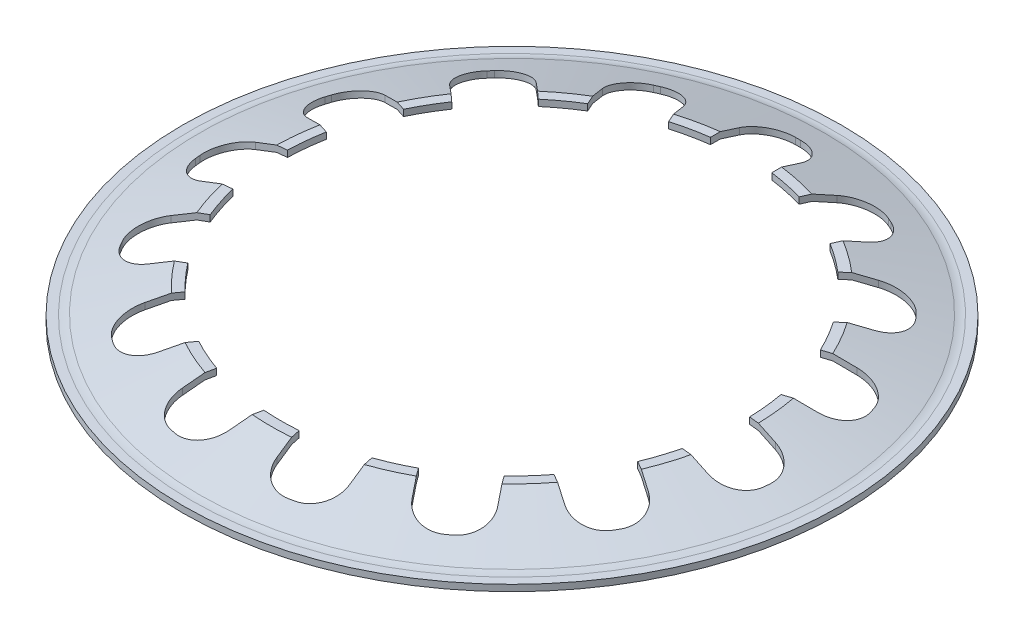
SolidWorks part; units mm, degrees
ref_plane "Plano frontal" through (0, 0, 0) normal (0, 0, 1) x (1, 0, 0)
ref_plane "Plano superior" through (0, 0, 0) normal (0, 1, 0) x (1, 0, 0)
ref_plane "Plano direito" through (0, 0, 0) normal (1, 0, 0) x (0, 0, -1)
sketch "Esboço1" plane through (0, 0, 0) normal (0, 0, 1) x (1, 0, 0)
  line L0 (0, -50.3288) -> (0, 62.2834) construction
  line L1 (47.1561, 13.2438) -> (62, 8.4938)
  line L2 (64.5, 8.4938) -> (64.5, 9.7438)
  line L3 (64.5, 9.7438) -> (62, 9.7438)
  line L4 (62, 9.7438) -> (47.1561, 14.4938)
  line L5 (47.1561, 14.4938) -> (45.25, 14.4938)
  line L6 (45.25, 14.4938) -> (45.25, 13.2438)
  line L7 (45.25, 13.2438) -> (47.1561, 13.2438)
  line L8 (62, 8.4938) -> (64.5, 8.4938)
  dimension "D1" = 1.25
  dimension "D2" = 1.25
  dimension "D3" = 64.5
  dimension "D4" = 45.25
  dimension "D5" = 62
  dimension "D6" = 62
  dimension "D7" = 6
revolve "Revolução1" add sketch "Esboço1" angle 360 about L0
sketch "Esboço3" plane through (0, 14.4938, 0) normal (0, 1, 0) x (1, 0, 0)
  line L0 (0, 56) -> (0, 0) construction
  line L1 (-0.5, 56) -> (0.5, 56)
  line L2 (-6, 50.5) -> (-6, 40.8262)
  line L3 (-6, 40.8262) -> (6, 40.8262)
  line L4 (6, 40.8262) -> (6, 50.5)
  line L5 (22.3205, 51.3619) -> (23.234, 50.9552)
  line L6 (15.0589, 48.5745) -> (11.1242, 39.737)
  line L7 (11.1242, 39.737) -> (22.0868, 34.8562)
  line L8 (22.0868, 34.8562) -> (26.0215, 43.6936)
  line L9 (41.2815, 37.8429) -> (41.9507, 37.0997)
  line L10 (33.514, 38.25) -> (26.325, 31.7769)
  line L11 (26.325, 31.7769) -> (34.3546, 22.8592)
  line L12 (34.3546, 22.8592) -> (41.5436, 29.3322)
  line L13 (53.1047, 17.7805) -> (53.4137, 16.8294)
  line L14 (46.1743, 21.3117) -> (36.9739, 18.3223)
  line L15 (36.9739, 18.3223) -> (40.6821, 6.9096)
  line L16 (40.6821, 6.9096) -> (49.8825, 9.899)
  line L17 (55.7455, -5.3563) -> (55.641, -6.3509)
  line L18 (50.8505, 0.6884) -> (41.2297, 1.6996)
  line L19 (41.2297, 1.6996) -> (39.9754, -10.2346)
  line L20 (39.9754, -10.2346) -> (49.5962, -11.2458)
  line L21 (48.7474, -27.567) -> (48.2474, -28.433)
  line L22 (46.7343, -20.0538) -> (38.3565, -15.2169)
  line L23 (38.3565, -15.2169) -> (32.3565, -25.6092)
  line L24 (32.3565, -25.6092) -> (40.7343, -30.4462)
  line L25 (33.3205, -45.0111) -> (32.5115, -45.5988)
  line L26 (34.5373, -37.3286) -> (28.8511, -29.5024)
  line L27 (28.8511, -29.5024) -> (19.1429, -36.5558)
  line L28 (19.1429, -36.5558) -> (24.8291, -44.3821)
  line L29 (12.1321, -54.6723) -> (11.154, -54.8802)
  line L30 (16.3684, -48.149) -> (14.3571, -38.6866)
  line L31 (14.3571, -38.6866) -> (2.6194, -41.1815)
  line L32 (2.6194, -41.1815) -> (4.6307, -50.6439)
  line L33 (-11.154, -54.8802) -> (-12.1321, -54.6723)
  line L34 (-4.6307, -50.6439) -> (-2.6194, -41.1815)
  line L35 (-2.6194, -41.1815) -> (-14.3571, -38.6866)
  line L36 (-14.3571, -38.6866) -> (-16.3684, -48.149)
  line L37 (-32.5115, -45.5988) -> (-33.3205, -45.0111)
  line L38 (-24.8291, -44.3821) -> (-19.1429, -36.5558)
  line L39 (-19.1429, -36.5558) -> (-28.8511, -29.5024)
  line L40 (-28.8511, -29.5024) -> (-34.5373, -37.3286)
  line L41 (-48.2474, -28.433) -> (-48.7474, -27.567)
  line L42 (-40.7343, -30.4462) -> (-32.3565, -25.6092)
  line L43 (-32.3565, -25.6092) -> (-38.3565, -15.2169)
  line L44 (-38.3565, -15.2169) -> (-46.7343, -20.0538)
  line L45 (-55.641, -6.3509) -> (-55.7455, -5.3563)
  line L46 (-49.5962, -11.2458) -> (-39.9754, -10.2346)
  line L47 (-39.9754, -10.2346) -> (-41.2297, 1.6996)
  line L48 (-41.2297, 1.6996) -> (-50.8505, 0.6884)
  line L49 (-53.4137, 16.8294) -> (-53.1047, 17.7805)
  line L50 (-49.8825, 9.899) -> (-40.6821, 6.9096)
  line L51 (-40.6821, 6.9096) -> (-36.9739, 18.3223)
  line L52 (-36.9739, 18.3223) -> (-46.1743, 21.3117)
  line L53 (-41.9507, 37.0997) -> (-41.2815, 37.8429)
  line L54 (-41.5436, 29.3322) -> (-34.3546, 22.8592)
  line L55 (-34.3546, 22.8592) -> (-26.325, 31.7769)
  line L56 (-26.325, 31.7769) -> (-33.514, 38.25)
  line L57 (-23.234, 50.9552) -> (-22.3205, 51.3619)
  line L58 (-26.0215, 43.6936) -> (-22.0868, 34.8562)
  line L59 (-22.0868, 34.8562) -> (-11.1242, 39.737)
  line L60 (-11.1242, 39.737) -> (-15.0589, 48.5745)
  arc A0 (0.5, 56) -> (6, 50.5) centre (0.5, 50.5) cw
  arc A1 (-0.5, 56) -> (-6, 50.5) centre (-0.5, 50.5) ccw
  arc A2 (23.234, 50.9552) -> (26.0215, 43.6936) centre (20.997, 45.9307) cw
  arc A3 (22.3205, 51.3619) -> (15.0589, 48.5745) centre (20.0834, 46.3374) ccw
  arc A4 (41.9507, 37.0997) -> (41.5436, 29.3322) centre (37.8634, 33.4195) cw
  arc A5 (41.2815, 37.8429) -> (33.514, 38.25) centre (37.1942, 34.1627) ccw
  arc A6 (53.4137, 16.8294) -> (49.8825, 9.899) centre (48.1829, 15.1298) cw
  arc A7 (53.1047, 17.7805) -> (46.1743, 21.3117) centre (47.8738, 16.0809) ccw
  arc A8 (55.641, -6.3509) -> (49.5962, -11.2458) centre (50.1711, -5.7759) cw
  arc A9 (55.7455, -5.3563) -> (50.8505, 0.6884) centre (50.2756, -4.7814) ccw
  arc A10 (48.2474, -28.433) -> (40.7343, -30.4462) centre (43.4843, -25.683) cw
  arc A11 (48.7474, -27.567) -> (46.7343, -20.0538) centre (43.9843, -24.817) ccw
  arc A12 (32.5115, -45.5988) -> (24.8291, -44.3821) centre (29.2786, -41.1493) cw
  arc A13 (33.3205, -45.0111) -> (34.5373, -37.3286) centre (30.0877, -40.5615) ccw
  arc A14 (11.154, -54.8802) -> (4.6307, -50.6439) centre (10.0105, -49.5004) cw
  arc A15 (12.1321, -54.6723) -> (16.3684, -48.149) centre (10.9886, -49.2925) ccw
  arc A16 (-12.1321, -54.6723) -> (-16.3684, -48.149) centre (-10.9886, -49.2925) cw
  arc A17 (-11.154, -54.8802) -> (-4.6307, -50.6439) centre (-10.0105, -49.5004) ccw
  arc A18 (-33.3205, -45.0111) -> (-34.5373, -37.3286) centre (-30.0877, -40.5615) cw
  arc A19 (-32.5115, -45.5988) -> (-24.8291, -44.3821) centre (-29.2786, -41.1493) ccw
  arc A20 (-48.7474, -27.567) -> (-46.7343, -20.0538) centre (-43.9843, -24.817) cw
  arc A21 (-48.2474, -28.433) -> (-40.7343, -30.4462) centre (-43.4843, -25.683) ccw
  arc A22 (-55.7455, -5.3563) -> (-50.8505, 0.6884) centre (-50.2756, -4.7814) cw
  arc A23 (-55.641, -6.3509) -> (-49.5962, -11.2458) centre (-50.1711, -5.7759) ccw
  arc A24 (-53.1047, 17.7805) -> (-46.1743, 21.3117) centre (-47.8738, 16.0809) cw
  arc A25 (-53.4137, 16.8294) -> (-49.8825, 9.899) centre (-48.1829, 15.1298) ccw
  arc A26 (-41.2815, 37.8429) -> (-33.514, 38.25) centre (-37.1942, 34.1627) cw
  arc A27 (-41.9507, 37.0997) -> (-41.5436, 29.3322) centre (-37.8634, 33.4195) ccw
  arc A28 (-22.3205, 51.3619) -> (-15.0589, 48.5745) centre (-20.0834, 46.3374) cw
  arc A29 (-23.234, 50.9552) -> (-26.0215, 43.6936) centre (-20.997, 45.9307) ccw
  point P125 (0, 0)
  dimension "D1" = 5.5
  dimension "D2" = 15
extrude "Corte-extrusão1" cut sketch "Esboço3" against normal through all
fillet "Filete1" radius 5 1 edges at (0, 9.7438, -62)
fillet "Filete2" radius 5 1 edges at (0, 8.4938, -62)
